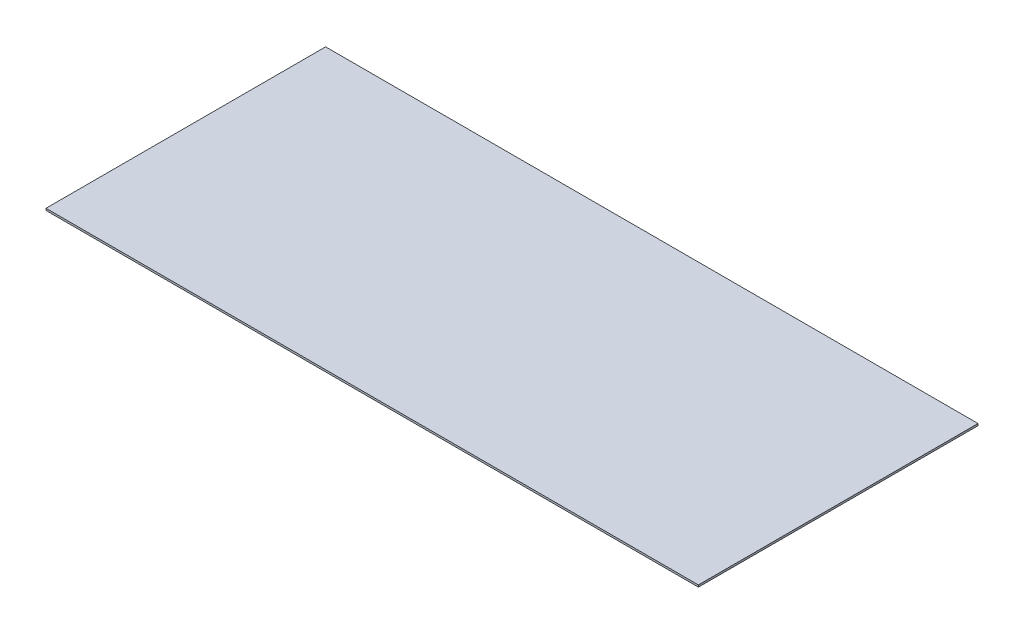
SolidWorks part; units mm, degrees
ref_plane "Front Plane" through (0, 0, 0) normal (0, 0, 1) x (1, 0, 0)
ref_plane "Top Plane" through (0, 0, 0) normal (0, 1, 0) x (1, 0, 0)
ref_plane "Right Plane" through (0, 0, 0) normal (1, 0, 0) x (0, 0, -1)
sketch "Sketch1" plane through (0, 0, 0) normal (0, 1, 0) x (1, 0, 0)
  line L1 (1066.8, -457.2) -> (-1066.8, -457.2)
  line L2 (1066.8, -457.2) -> (1066.8, 457.2)
  line L3 (1066.8, 457.2) -> (-1066.8, 457.2)
  line L4 (-1066.8, -457.2) -> (-1066.8, 457.2)
  line L5 (1066.8, -457.2) -> (-1066.8, 457.2) construction
  line L6 (1066.8, 457.2) -> (-1066.8, -457.2) construction
  point P0 (0, 0)
  dimension "D1" = 2133.6
  dimension "D2" = 914.4
extrude "Boss-Extrude1" add sketch "Sketch1" along normal blind 6.35
